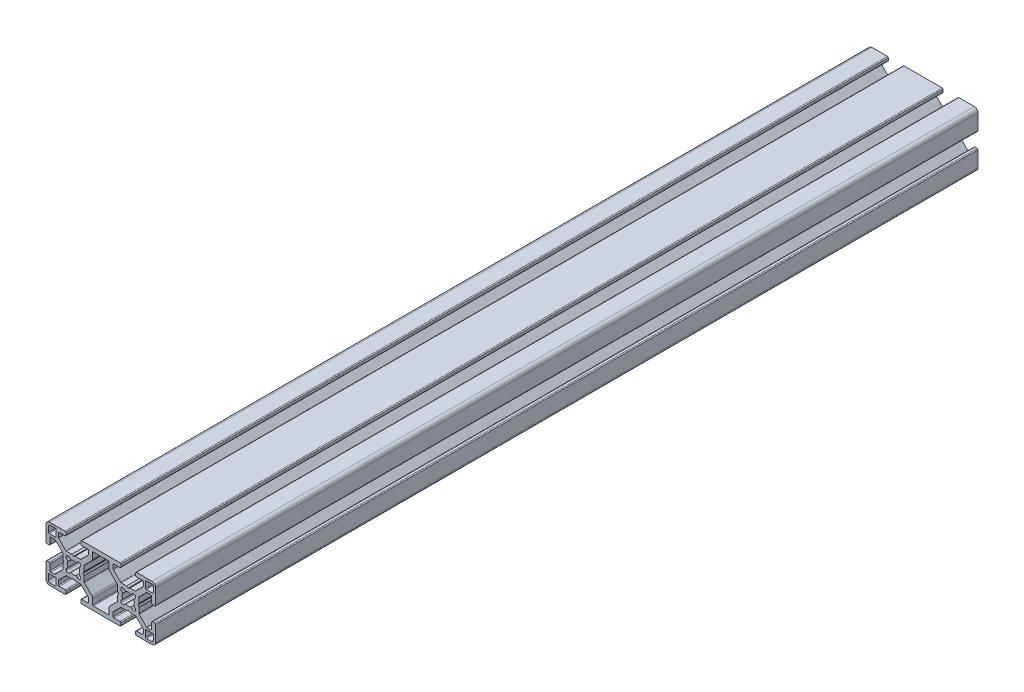
SolidWorks part; units mm, degrees
material "6105-T5 Aluminum"
ref_plane "Front Plane" through (0, 0, 0) normal (0, 0, 1) x (1, 0, 0)
ref_plane "Top Plane" through (0, 0, 0) normal (0, 1, 0) x (1, 0, 0)
ref_plane "Right Plane" through (0, 0, 0) normal (1, 0, 0) x (0, 0, -1)
sketch "Sketch1" plane through (0, 0, 0) normal (0, 0, 1) x (1, 0, 0)
  line L0 (12.7825, 3.7261) -> (13.5257, 2.983)
  line L1 (16.4743, 2.983) -> (17.2175, 3.7261)
  line L2 (18.7261, 2.2175) -> (17.983, 1.4743)
  line L3 (17.983, -1.4743) -> (18.7261, -2.2175)
  line L4 (17.2175, -3.7261) -> (16.4743, -2.983)
  line L5 (13.5257, -2.983) -> (12.7825, -3.7261)
  line L6 (11.2739, -2.2175) -> (12.017, -1.4743)
  line L7 (12.017, 1.4743) -> (11.2739, 2.2175)
  line L8 (-28.7046, 9.8946) -> (-28.7046, 12.6886)
  line L9 (-27.6886, 13.7046) -> (-24.8946, 13.7046)
  line L10 (-24.5136, 13.3236) -> (-24.5136, 9.8946)
  line L11 (-24.8946, 9.5136) -> (-28.3236, 9.5136)
  line L12 (-24.8946, -13.7046) -> (-27.6886, -13.7046)
  line L13 (-28.7046, -12.6886) -> (-28.7046, -9.8946)
  line L14 (-28.3236, -9.5136) -> (-24.8946, -9.5136)
  line L15 (-24.5136, -9.8946) -> (-24.5136, -13.3236)
  line L16 (4.9816, 8.2224) -> (9.0292, 4.1748)
  line L17 (9.178, 3.8155) -> (9.178, 0.9525)
  line L18 (9.178, 0.9525) -> (9.686, 0)
  line L19 (9.686, 0) -> (9.178, -0.9525)
  line L20 (9.178, -0.9525) -> (9.178, -3.8155)
  line L21 (9.0292, -4.1748) -> (4.9816, -8.2224)
  line L22 (4.5352, -9.3) -> (4.5352, -12.4092)
  line L23 (4.1542, -12.7902) -> (-4.1542, -12.7902)
  line L24 (-4.5352, -12.4092) -> (-4.5352, -9.3)
  line L25 (-4.9816, -8.2224) -> (-9.0292, -4.1748)
  line L26 (-9.178, -3.8155) -> (-9.178, -0.9525)
  line L27 (-9.178, -0.9525) -> (-9.686, 0)
  line L28 (-9.686, 0) -> (-9.178, 0.9525)
  line L29 (-9.178, 0.9525) -> (-9.178, 3.8155)
  line L30 (-9.0292, 4.1748) -> (-4.9816, 8.2224)
  line L31 (-4.5352, 9.3) -> (-4.5352, 12.4092)
  line L32 (-4.1542, 12.7902) -> (4.1542, 12.7902)
  line L33 (4.5352, 12.4092) -> (4.5352, 9.3)
  line L34 (-18.7261, -2.2175) -> (-17.983, -1.4743)
  line L35 (-17.983, 1.4743) -> (-18.7261, 2.2175)
  line L36 (-17.2175, 3.7261) -> (-16.4743, 2.983)
  line L37 (-13.5257, 2.983) -> (-12.7825, 3.7261)
  line L38 (-11.2739, 2.2175) -> (-12.017, 1.4743)
  line L39 (-12.017, -1.4743) -> (-11.2739, -2.2175)
  line L40 (-12.7825, -3.7261) -> (-13.5257, -2.983)
  line L41 (-16.4743, -2.983) -> (-17.2175, -3.7261)
  line L42 (24.8946, 13.7046) -> (27.6886, 13.7046)
  line L43 (28.7046, 12.6886) -> (28.7046, 9.8946)
  line L44 (28.3236, 9.5136) -> (24.8946, 9.5136)
  line L45 (24.5136, 9.8946) -> (24.5136, 13.3236)
  line L46 (24.5136, -13.3236) -> (24.5136, -9.8946)
  line L47 (24.8946, -9.5136) -> (28.3236, -9.5136)
  line L48 (28.7046, -9.8946) -> (28.7046, -12.6886)
  line L49 (27.6886, -13.7046) -> (24.8946, -13.7046)
  line L50 (-10.428, -15) -> (10.428, -15)
  line L51 (10.936, -14.492) -> (10.936, -13.2982)
  line L52 (10.428, -12.7902) -> (7.253, -12.7902)
  line L53 (6.745, -12.2822) -> (6.745, -10.2615)
  line L54 (6.8938, -9.9023) -> (10.8252, -5.9708)
  line L55 (11.1845, -5.822) -> (14.0475, -5.822)
  line L56 (14.0475, -5.822) -> (15, -5.314)
  line L57 (15, -5.314) -> (15.9525, -5.822)
  line L58 (15.9525, -5.822) -> (18.8155, -5.822)
  line L59 (19.1748, -5.9708) -> (23.1062, -9.9023)
  line L60 (23.255, -10.2615) -> (23.255, -12.2822)
  line L61 (22.747, -12.7902) -> (19.572, -12.7902)
  line L62 (19.064, -13.2982) -> (19.064, -14.492)
  line L63 (19.572, -15) -> (27.9934, -15)
  line L64 (30, -12.9934) -> (30, -4.572)
  line L65 (29.492, -4.064) -> (28.2982, -4.064)
  line L66 (27.7902, -4.572) -> (27.7902, -7.747)
  line L67 (27.2822, -8.255) -> (25.2615, -8.255)
  line L68 (24.9023, -8.1062) -> (20.9708, -4.1748)
  line L69 (20.822, -3.8155) -> (20.822, -0.9525)
  line L70 (20.822, -0.9525) -> (20.314, 0)
  line L71 (20.314, 0) -> (20.822, 0.9525)
  line L72 (20.822, 0.9525) -> (20.822, 3.8155)
  line L73 (20.9708, 4.1748) -> (24.9023, 8.1062)
  line L74 (25.2615, 8.255) -> (27.2822, 8.255)
  line L75 (27.7902, 7.747) -> (27.7902, 4.572)
  line L76 (28.2982, 4.064) -> (29.492, 4.064)
  line L77 (30, 4.572) -> (30, 12.9934)
  line L78 (27.9934, 15) -> (19.572, 15)
  line L79 (19.064, 14.492) -> (19.064, 13.2982)
  line L80 (19.572, 12.7902) -> (22.747, 12.7902)
  line L81 (23.255, 12.2822) -> (23.255, 10.2615)
  line L82 (23.1062, 9.9023) -> (19.1748, 5.9708)
  line L83 (18.8155, 5.822) -> (15.9525, 5.822)
  line L84 (15.9525, 5.822) -> (15, 5.314)
  line L85 (15, 5.314) -> (14.0475, 5.822)
  line L86 (14.0475, 5.822) -> (11.1845, 5.822)
  line L87 (10.8252, 5.9708) -> (6.8938, 9.9023)
  line L88 (6.745, 10.2615) -> (6.745, 12.2822)
  line L89 (7.253, 12.7902) -> (10.428, 12.7902)
  line L90 (10.936, 13.2982) -> (10.936, 14.492)
  line L91 (10.428, 15) -> (-10.428, 15)
  line L92 (-10.936, 14.492) -> (-10.936, 13.2982)
  line L93 (-10.428, 12.7902) -> (-7.253, 12.7902)
  line L94 (-6.745, 12.2822) -> (-6.745, 10.2615)
  line L95 (-6.8938, 9.9023) -> (-10.8252, 5.9708)
  line L96 (-11.1845, 5.822) -> (-14.0475, 5.822)
  line L97 (-14.0475, 5.822) -> (-15, 5.314)
  line L98 (-15, 5.314) -> (-15.9525, 5.822)
  line L99 (-15.9525, 5.822) -> (-18.8155, 5.822)
  line L100 (-19.1748, 5.9708) -> (-23.1062, 9.9023)
  line L101 (-23.255, 10.2615) -> (-23.255, 12.2822)
  line L102 (-22.747, 12.7902) -> (-19.572, 12.7902)
  line L103 (-19.064, 13.2982) -> (-19.064, 14.492)
  line L104 (-19.572, 15) -> (-27.9934, 15)
  line L105 (-30, 12.9934) -> (-30, 4.572)
  line L106 (-29.492, 4.064) -> (-28.2982, 4.064)
  line L107 (-27.7902, 4.572) -> (-27.7902, 7.747)
  line L108 (-27.2822, 8.255) -> (-25.2615, 8.255)
  line L109 (-24.9023, 8.1062) -> (-20.9708, 4.1748)
  line L110 (-20.822, 3.8155) -> (-20.822, 0.9525)
  line L111 (-20.822, 0.9525) -> (-20.314, 0)
  line L112 (-20.314, 0) -> (-20.822, -0.9525)
  line L113 (-20.822, -0.9525) -> (-20.822, -3.8155)
  line L114 (-20.9708, -4.1748) -> (-24.9023, -8.1062)
  line L115 (-25.2615, -8.255) -> (-27.2822, -8.255)
  line L116 (-27.7902, -7.747) -> (-27.7902, -4.572)
  line L117 (-28.2982, -4.064) -> (-29.492, -4.064)
  line L118 (-30, -4.572) -> (-30, -12.9934)
  line L119 (-27.9934, -15) -> (-19.572, -15)
  line L120 (-19.064, -14.492) -> (-19.064, -13.2982)
  line L121 (-19.572, -12.7902) -> (-22.747, -12.7902)
  line L122 (-23.255, -12.2822) -> (-23.255, -10.2615)
  line L123 (-23.1062, -9.9023) -> (-19.1748, -5.9708)
  line L124 (-18.8155, -5.822) -> (-15.9525, -5.822)
  line L125 (-15.9525, -5.822) -> (-15, -5.314)
  line L126 (-15, -5.314) -> (-14.0475, -5.822)
  line L127 (-14.0475, -5.822) -> (-11.1845, -5.822)
  line L128 (-10.8252, -5.9708) -> (-6.8938, -9.9023)
  line L129 (-6.745, -10.2615) -> (-6.745, -12.2822)
  line L130 (-7.253, -12.7902) -> (-10.428, -12.7902)
  line L131 (-10.936, -13.2982) -> (-10.936, -14.492)
  arc A0 (12.7825, 3.7261) -> (11.2739, 2.2175) centre (12.0282, 2.9718) ccw
  arc A1 (16.4743, 2.983) -> (13.5257, 2.983) centre (15, 0) ccw
  arc A2 (18.7261, 2.2175) -> (17.2175, 3.7261) centre (17.9718, 2.9718) ccw
  arc A3 (17.983, -1.4743) -> (17.983, 1.4743) centre (15, 0) ccw
  arc A4 (17.2175, -3.7261) -> (18.7261, -2.2175) centre (17.9718, -2.9718) ccw
  arc A5 (13.5257, -2.983) -> (16.4743, -2.983) centre (15, 0) ccw
  arc A6 (11.2739, -2.2175) -> (12.7825, -3.7261) centre (12.0282, -2.9718) ccw
  arc A7 (12.017, 1.4743) -> (12.017, -1.4743) centre (15, 0) ccw
  arc A8 (-28.7046, 9.8946) -> (-28.3236, 9.5136) centre (-28.3236, 9.8946) ccw
  arc A9 (-27.6886, 13.7046) -> (-28.7046, 12.6886) centre (-27.6886, 12.6886) ccw
  arc A10 (-24.5136, 13.3236) -> (-24.8946, 13.7046) centre (-24.8946, 13.3236) ccw
  arc A11 (-24.8946, 9.5136) -> (-24.5136, 9.8946) centre (-24.8946, 9.8946) ccw
  arc A12 (-24.8946, -13.7046) -> (-24.5136, -13.3236) centre (-24.8946, -13.3236) ccw
  arc A13 (-28.7046, -12.6886) -> (-27.6886, -13.7046) centre (-27.6886, -12.6886) ccw
  arc A14 (-28.3236, -9.5136) -> (-28.7046, -9.8946) centre (-28.3236, -9.8946) ccw
  arc A15 (-24.5136, -9.8946) -> (-24.8946, -9.5136) centre (-24.8946, -9.8946) ccw
  arc A16 (4.5352, 9.3) -> (4.9816, 8.2224) centre (6.0592, 9.3) ccw
  arc A17 (9.178, 3.8155) -> (9.0292, 4.1748) centre (8.67, 3.8155) ccw
  arc A18 (9.0292, -4.1748) -> (9.178, -3.8155) centre (8.67, -3.8155) ccw
  arc A19 (4.9816, -8.2224) -> (4.5352, -9.3) centre (6.0592, -9.3) ccw
  arc A20 (4.1542, -12.7902) -> (4.5352, -12.4092) centre (4.1542, -12.4092) ccw
  arc A21 (-4.5352, -12.4092) -> (-4.1542, -12.7902) centre (-4.1542, -12.4092) ccw
  arc A22 (-4.5352, -9.3) -> (-4.9816, -8.2224) centre (-6.0592, -9.3) ccw
  arc A23 (-9.178, -3.8155) -> (-9.0292, -4.1748) centre (-8.67, -3.8155) ccw
  arc A24 (-9.0292, 4.1748) -> (-9.178, 3.8155) centre (-8.67, 3.8155) ccw
  arc A25 (-4.9816, 8.2224) -> (-4.5352, 9.3) centre (-6.0592, 9.3) ccw
  arc A26 (-4.1542, 12.7902) -> (-4.5352, 12.4092) centre (-4.1542, 12.4092) ccw
  arc A27 (4.5352, 12.4092) -> (4.1542, 12.7902) centre (4.1542, 12.4092) ccw
  arc A28 (-18.7261, -2.2175) -> (-17.2175, -3.7261) centre (-17.9718, -2.9718) ccw
  arc A29 (-17.983, 1.4743) -> (-17.983, -1.4743) centre (-15, 0) ccw
  arc A30 (-17.2175, 3.7261) -> (-18.7261, 2.2175) centre (-17.9718, 2.9718) ccw
  arc A31 (-13.5257, 2.983) -> (-16.4743, 2.983) centre (-15, 0) ccw
  arc A32 (-11.2739, 2.2175) -> (-12.7825, 3.7261) centre (-12.0282, 2.9718) ccw
  arc A33 (-12.017, -1.4743) -> (-12.017, 1.4743) centre (-15, 0) ccw
  arc A34 (-12.7825, -3.7261) -> (-11.2739, -2.2175) centre (-12.0282, -2.9718) ccw
  arc A35 (-16.4743, -2.983) -> (-13.5257, -2.983) centre (-15, 0) ccw
  arc A36 (24.8946, 13.7046) -> (24.5136, 13.3236) centre (24.8946, 13.3236) ccw
  arc A37 (28.7046, 12.6886) -> (27.6886, 13.7046) centre (27.6886, 12.6886) ccw
  arc A38 (28.3236, 9.5136) -> (28.7046, 9.8946) centre (28.3236, 9.8946) ccw
  arc A39 (24.5136, 9.8946) -> (24.8946, 9.5136) centre (24.8946, 9.8946) ccw
  arc A40 (24.5136, -13.3236) -> (24.8946, -13.7046) centre (24.8946, -13.3236) ccw
  arc A41 (24.8946, -9.5136) -> (24.5136, -9.8946) centre (24.8946, -9.8946) ccw
  arc A42 (28.7046, -9.8946) -> (28.3236, -9.5136) centre (28.3236, -9.8946) ccw
  arc A43 (27.6886, -13.7046) -> (28.7046, -12.6886) centre (27.6886, -12.6886) ccw
  arc A44 (10.428, -15) -> (10.936, -14.492) centre (10.428, -14.492) ccw
  arc A45 (10.936, -13.2982) -> (10.428, -12.7902) centre (10.428, -13.2982) ccw
  arc A46 (6.745, -12.2822) -> (7.253, -12.7902) centre (7.253, -12.2822) ccw
  arc A47 (6.8938, -9.9023) -> (6.745, -10.2615) centre (7.253, -10.2615) ccw
  arc A48 (11.1845, -5.822) -> (10.8252, -5.9708) centre (11.1845, -6.33) ccw
  arc A49 (19.1748, -5.9708) -> (18.8155, -5.822) centre (18.8155, -6.33) ccw
  arc A50 (23.255, -10.2615) -> (23.1062, -9.9023) centre (22.747, -10.2615) ccw
  arc A51 (22.747, -12.7902) -> (23.255, -12.2822) centre (22.747, -12.2822) ccw
  arc A52 (19.572, -12.7902) -> (19.064, -13.2982) centre (19.572, -13.2982) ccw
  arc A53 (19.064, -14.492) -> (19.572, -15) centre (19.572, -14.492) ccw
  arc A54 (27.9934, -15) -> (30, -12.9934) centre (27.9934, -12.9934) ccw
  arc A55 (30, -4.572) -> (29.492, -4.064) centre (29.492, -4.572) ccw
  arc A56 (28.2982, -4.064) -> (27.7902, -4.572) centre (28.2982, -4.572) ccw
  arc A57 (27.2822, -8.255) -> (27.7902, -7.747) centre (27.2822, -7.747) ccw
  arc A58 (24.9023, -8.1062) -> (25.2615, -8.255) centre (25.2615, -7.747) ccw
  arc A59 (20.822, -3.8155) -> (20.9708, -4.1748) centre (21.33, -3.8155) ccw
  arc A60 (20.9708, 4.1748) -> (20.822, 3.8155) centre (21.33, 3.8155) ccw
  arc A61 (25.2615, 8.255) -> (24.9023, 8.1062) centre (25.2615, 7.747) ccw
  arc A62 (27.7902, 7.747) -> (27.2822, 8.255) centre (27.2822, 7.747) ccw
  arc A63 (27.7902, 4.572) -> (28.2982, 4.064) centre (28.2982, 4.572) ccw
  arc A64 (29.492, 4.064) -> (30, 4.572) centre (29.492, 4.572) ccw
  arc A65 (30, 12.9934) -> (27.9934, 15) centre (27.9934, 12.9934) ccw
  arc A66 (19.572, 15) -> (19.064, 14.492) centre (19.572, 14.492) ccw
  arc A67 (19.064, 13.2982) -> (19.572, 12.7902) centre (19.572, 13.2982) ccw
  arc A68 (23.255, 12.2822) -> (22.747, 12.7902) centre (22.747, 12.2822) ccw
  arc A69 (23.1062, 9.9023) -> (23.255, 10.2615) centre (22.747, 10.2615) ccw
  arc A70 (18.8155, 5.822) -> (19.1748, 5.9708) centre (18.8155, 6.33) ccw
  arc A71 (10.8252, 5.9708) -> (11.1845, 5.822) centre (11.1845, 6.33) ccw
  arc A72 (6.745, 10.2615) -> (6.8938, 9.9023) centre (7.253, 10.2615) ccw
  arc A73 (7.253, 12.7902) -> (6.745, 12.2822) centre (7.253, 12.2822) ccw
  arc A74 (10.428, 12.7902) -> (10.936, 13.2982) centre (10.428, 13.2982) ccw
  arc A75 (10.936, 14.492) -> (10.428, 15) centre (10.428, 14.492) ccw
  arc A76 (-10.428, 15) -> (-10.936, 14.492) centre (-10.428, 14.492) ccw
  arc A77 (-10.936, 13.2982) -> (-10.428, 12.7902) centre (-10.428, 13.2982) ccw
  arc A78 (-6.745, 12.2822) -> (-7.253, 12.7902) centre (-7.253, 12.2822) ccw
  arc A79 (-6.8938, 9.9023) -> (-6.745, 10.2615) centre (-7.253, 10.2615) ccw
  arc A80 (-11.1845, 5.822) -> (-10.8252, 5.9708) centre (-11.1845, 6.33) ccw
  arc A81 (-19.1748, 5.9708) -> (-18.8155, 5.822) centre (-18.8155, 6.33) ccw
  arc A82 (-23.255, 10.2615) -> (-23.1062, 9.9023) centre (-22.747, 10.2615) ccw
  arc A83 (-22.747, 12.7902) -> (-23.255, 12.2822) centre (-22.747, 12.2822) ccw
  arc A84 (-19.572, 12.7902) -> (-19.064, 13.2982) centre (-19.572, 13.2982) ccw
  arc A85 (-19.064, 14.492) -> (-19.572, 15) centre (-19.572, 14.492) ccw
  arc A86 (-27.9934, 15) -> (-30, 12.9934) centre (-27.9934, 12.9934) ccw
  arc A87 (-30, 4.572) -> (-29.492, 4.064) centre (-29.492, 4.572) ccw
  arc A88 (-28.2982, 4.064) -> (-27.7902, 4.572) centre (-28.2982, 4.572) ccw
  arc A89 (-27.2822, 8.255) -> (-27.7902, 7.747) centre (-27.2822, 7.747) ccw
  arc A90 (-24.9023, 8.1062) -> (-25.2615, 8.255) centre (-25.2615, 7.747) ccw
  arc A91 (-20.822, 3.8155) -> (-20.9708, 4.1748) centre (-21.33, 3.8155) ccw
  arc A92 (-20.9708, -4.1748) -> (-20.822, -3.8155) centre (-21.33, -3.8155) ccw
  arc A93 (-25.2615, -8.255) -> (-24.9023, -8.1062) centre (-25.2615, -7.747) ccw
  arc A94 (-27.7902, -7.747) -> (-27.2822, -8.255) centre (-27.2822, -7.747) ccw
  arc A95 (-27.7902, -4.572) -> (-28.2982, -4.064) centre (-28.2982, -4.572) ccw
  arc A96 (-29.492, -4.064) -> (-30, -4.572) centre (-29.492, -4.572) ccw
  arc A97 (-30, -12.9934) -> (-27.9934, -15) centre (-27.9934, -12.9934) ccw
  arc A98 (-19.572, -15) -> (-19.064, -14.492) centre (-19.572, -14.492) ccw
  arc A99 (-19.064, -13.2982) -> (-19.572, -12.7902) centre (-19.572, -13.2982) ccw
  arc A100 (-23.255, -12.2822) -> (-22.747, -12.7902) centre (-22.747, -12.2822) ccw
  arc A101 (-23.1062, -9.9023) -> (-23.255, -10.2615) centre (-22.747, -10.2615) ccw
  arc A102 (-18.8155, -5.822) -> (-19.1748, -5.9708) centre (-18.8155, -6.33) ccw
  arc A103 (-10.8252, -5.9708) -> (-11.1845, -5.822) centre (-11.1845, -6.33) ccw
  arc A104 (-6.745, -10.2615) -> (-6.8938, -9.9023) centre (-7.253, -10.2615) ccw
  arc A105 (-7.253, -12.7902) -> (-6.745, -12.2822) centre (-7.253, -12.2822) ccw
  arc A106 (-10.428, -12.7902) -> (-10.936, -13.2982) centre (-10.428, -13.2982) ccw
  arc A107 (-10.936, -14.492) -> (-10.428, -15) centre (-10.428, -14.492) ccw
extrude "Extrude1" add sketch "Sketch1" against normal blind 450
